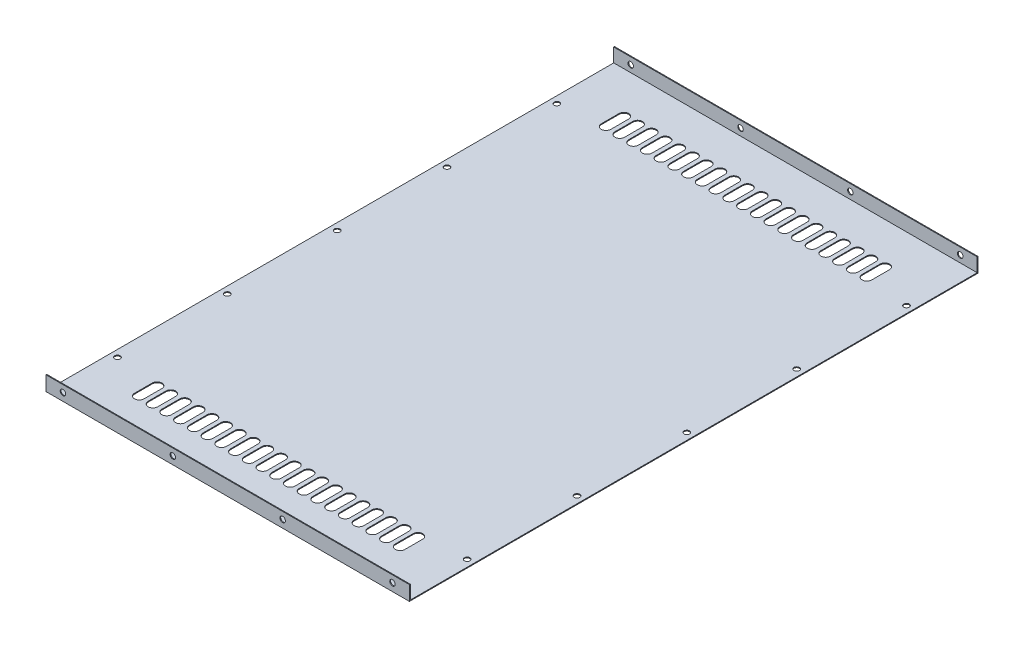
SolidWorks part; units mm, degrees
material "AISI 316 Нержавеющая сталь, лист (SS)"
ref_plane "Спереди" through (0, 0, 0) normal (0, 0, 1) x (1, 0, 0)
ref_plane "Сверху" through (0, 0, 0) normal (0, 1, 0) x (1, 0, 0)
ref_plane "Справа" through (0, 0, 0) normal (1, 0, 0) x (0, 0, -1)
other "Configuration Table"
sketch "Эскиз1" plane through (0, 0, 0) normal (0, 1, 0) x (1, 0, 0)
  line L0 (0, -207.05) -> (0, 207.05) construction
  line L1 (-132.35, 207.05) -> (132.35, 207.05)
  line L2 (-132.35, 207.05) -> (-132.35, -207.05)
  line L3 (-132.35, -207.05) -> (132.35, -207.05)
  line L4 (132.35, 207.05) -> (132.35, -207.05)
  line L5 (-132.35, 0) -> (132.35, 0) construction
  dimension "D1" = 414.1
  dimension "D2" = 264.7
extrude "Бобышка-Вытянуть1" add sketch "Эскиз1" along normal blind 0.6
sketch "Эскиз2" plane through (132.35, 0, 0) normal (1, 0, 0) x (0, 0, -1)
  line L1 (-207.05, 0) -> (-206.45, 0)
  line L2 (-207.05, 0) -> (-207.05, 10.6)
  line L3 (-207.05, 10.6) -> (-206.45, 10.6)
  line L4 (-206.45, 0) -> (-206.45, 10.6)
  line L5 (207.05, 0) -> (206.45, 0)
  line L6 (207.05, 0) -> (207.05, 10.6)
  line L7 (207.05, 10.6) -> (206.45, 10.6)
  line L8 (206.45, 0) -> (206.45, 10.6)
  dimension "D1" = 0.6
  dimension "D2" = 10.6
  dimension "D3" = 0.6
  dimension "D4" = 10.6
extrude "Бобышка-Вытянуть2" add sketch "Эскиз2" against normal up to surface (264.7 mm away) up to face at (-132.35, 0.3, 0)
sketch "Эскиз6" plane through (0, 0.6, 0) normal (0, 1, 0) x (1, 0, 0)
  line L0 (-132.35, 206.45) -> (-132.35, -206.45) construction
  line L1 (-132.35, -197.05) -> (-122.35, -197.05)
  line L2 (-132.35, -197.05) -> (-132.35, 197.05)
  line L3 (-132.35, 197.05) -> (-122.35, 197.05)
  line L4 (-122.35, -197.05) -> (-122.35, 197.05)
  line L5 (-132.35, 207.05) -> (132.35, 207.05) construction
  line L6 (-132.35, -207.05) -> (132.35, -207.05) construction
  line L7 (-127.35, -197.05) -> (-127.35, 197.05) construction
  line L8 (-132.35, 0) -> (-122.35, 0) construction
  line L9 (122.35, -197.05) -> (132.35, -197.05)
  line L10 (122.35, -197.05) -> (122.35, 197.05)
  line L11 (122.35, 197.05) -> (132.35, 197.05)
  line L12 (132.35, -197.05) -> (132.35, 197.05)
  line L13 (127.35, -197.05) -> (127.35, 197.05) construction
  line L14 (122.35, 0) -> (132.35, 0) construction
  line L15 (132.35, -206.45) -> (132.35, 206.45) construction
  circle A0 centre (-127.35, -160) radius 2
  circle A1 centre (-127.35, -80) radius 2
  circle A2 centre (-127.35, 0) radius 2
  circle A3 centre (-127.35, 80) radius 2
  circle A4 centre (-127.35, 160) radius 2
  circle A5 centre (127.35, -160) radius 2
  circle A6 centre (127.35, -80) radius 2
  circle A7 centre (127.35, 0) radius 2
  circle A8 centre (127.35, 80) radius 2
  circle A9 centre (127.35, 160) radius 2
  dimension "D4" = 4
  dimension "D7" = 4
  dimension "D1" = 10
  dimension "D2" = 10
  dimension "D3" = 10
  dimension "D6" = 80
  dimension "D8" = 80
  dimension "D9" = 10
  dimension "D10" = 10
  dimension "D11" = 10
  dimension "D12" = 80
  dimension "D13" = 80
  dimension "D14" = 80
  dimension "D5" = 5
extrude "Вырез-Вытянуть1" cut sketch "Эскиз6" against normal through all contours A6 | A5 | A7 | A8 | A9 | A1 | A2 | A0 | A3 | A4
sketch "Эскиз7" plane through (0, 0, -207.05) normal (0, 0, -1) x (-1, 0, 0)
  line L0 (-132.35, 0.6) -> (132.35, 0.6)
  line L1 (-132.35, 10.6) -> (-132.35, 0) construction
  line L2 (132.35, 10.6) -> (132.35, 0) construction
  line L3 (132.35, 10.6) -> (-132.35, 10.6) construction
  line L4 (-132.35, 5.6) -> (132.35, 5.6) construction
  line L5 (0, 10.6) -> (0, 0.6) construction
  circle A0 centre (-120, 5.6) radius 2
  circle A1 centre (-40, 5.6) radius 2
  circle A2 centre (40, 5.6) radius 2
  circle A3 centre (120, 5.6) radius 2
  dimension "D2" = 4
  dimension "D1" = 10
  dimension "D4" = 80
  dimension "D3" = 4
extrude "Вырез-Вытянуть2" cut sketch "Эскиз7" against normal up to surface (414.1 mm away) contours A0 | A1 | A2 | A3 up to face at (0, 5.3, 207.05)
sketch "Эскиз8" plane through (0, 0.6, 0) normal (0, 1, 0) x (1, 0, 0)
  line L0 (-95, 176.5) -> (-95, 163.5) construction
  line L1 (-91.5, 176.5) -> (-91.5, 163.5)
  line L2 (-98.5, 176.5) -> (-98.5, 163.5)
  line L3 (-85, 176.5) -> (-85, 163.5) construction
  line L4 (-81.5, 176.5) -> (-81.5, 163.5)
  line L5 (-88.5, 176.5) -> (-88.5, 163.5)
  line L6 (-75, 176.5) -> (-75, 163.5) construction
  line L7 (-71.5, 176.5) -> (-71.5, 163.5)
  line L8 (-78.5, 176.5) -> (-78.5, 163.5)
  line L9 (-65, 176.5) -> (-65, 163.5) construction
  line L10 (-61.5, 176.5) -> (-61.5, 163.5)
  line L11 (-68.5, 176.5) -> (-68.5, 163.5)
  line L12 (-55, 176.5) -> (-55, 163.5) construction
  line L13 (-51.5, 176.5) -> (-51.5, 163.5)
  line L14 (-58.5, 176.5) -> (-58.5, 163.5)
  line L15 (-45, 176.5) -> (-45, 163.5) construction
  line L16 (-41.5, 176.5) -> (-41.5, 163.5)
  line L17 (-48.5, 176.5) -> (-48.5, 163.5)
  line L18 (-35, 176.5) -> (-35, 163.5) construction
  line L19 (-31.5, 176.5) -> (-31.5, 163.5)
  line L20 (-38.5, 176.5) -> (-38.5, 163.5)
  line L21 (-25, 176.5) -> (-25, 163.5) construction
  line L22 (-21.5, 176.5) -> (-21.5, 163.5)
  line L23 (-28.5, 176.5) -> (-28.5, 163.5)
  line L24 (-15, 176.5) -> (-15, 163.5) construction
  line L25 (-11.5, 176.5) -> (-11.5, 163.5)
  line L26 (-18.5, 176.5) -> (-18.5, 163.5)
  line L27 (-5, 176.5) -> (-5, 163.5) construction
  line L28 (-1.5, 176.5) -> (-1.5, 163.5)
  line L29 (-8.5, 176.5) -> (-8.5, 163.5)
  line L30 (5, 176.5) -> (5, 163.5) construction
  line L31 (8.5, 176.5) -> (8.5, 163.5)
  line L32 (1.5, 176.5) -> (1.5, 163.5)
  line L33 (15, 176.5) -> (15, 163.5) construction
  line L34 (18.5, 176.5) -> (18.5, 163.5)
  line L35 (11.5, 176.5) -> (11.5, 163.5)
  line L36 (25, 176.5) -> (25, 163.5) construction
  line L37 (28.5, 176.5) -> (28.5, 163.5)
  line L38 (21.5, 176.5) -> (21.5, 163.5)
  line L39 (35, 176.5) -> (35, 163.5) construction
  line L40 (38.5, 176.5) -> (38.5, 163.5)
  line L41 (31.5, 176.5) -> (31.5, 163.5)
  line L42 (45, 176.5) -> (45, 163.5) construction
  line L43 (48.5, 176.5) -> (48.5, 163.5)
  line L44 (41.5, 176.5) -> (41.5, 163.5)
  line L45 (55, 176.5) -> (55, 163.5) construction
  line L46 (58.5, 176.5) -> (58.5, 163.5)
  line L47 (51.5, 176.5) -> (51.5, 163.5)
  line L48 (65, 176.5) -> (65, 163.5) construction
  line L49 (68.5, 176.5) -> (68.5, 163.5)
  line L50 (61.5, 176.5) -> (61.5, 163.5)
  line L51 (75, 176.5) -> (75, 163.5) construction
  line L52 (78.5, 176.5) -> (78.5, 163.5)
  line L53 (71.5, 176.5) -> (71.5, 163.5)
  line L54 (85, 176.5) -> (85, 163.5) construction
  line L55 (88.5, 176.5) -> (88.5, 163.5)
  line L56 (81.5, 176.5) -> (81.5, 163.5)
  line L57 (95, 176.5) -> (95, 163.5) construction
  line L58 (98.5, 176.5) -> (98.5, 163.5)
  line L59 (91.5, 176.5) -> (91.5, 163.5)
  line L60 (-85, -163.5) -> (-85, -176.5) construction
  line L61 (-81.5, -163.5) -> (-81.5, -176.5)
  line L62 (-88.5, -163.5) -> (-88.5, -176.5)
  line L63 (-75, -163.5) -> (-75, -176.5) construction
  line L64 (-71.5, -163.5) -> (-71.5, -176.5)
  line L65 (-78.5, -163.5) -> (-78.5, -176.5)
  line L66 (-65, -163.5) -> (-65, -176.5) construction
  line L67 (-61.5, -163.5) -> (-61.5, -176.5)
  line L68 (-68.5, -163.5) -> (-68.5, -176.5)
  line L69 (-55, -163.5) -> (-55, -176.5) construction
  line L70 (-51.5, -163.5) -> (-51.5, -176.5)
  line L71 (-58.5, -163.5) -> (-58.5, -176.5)
  line L72 (-45, -163.5) -> (-45, -176.5) construction
  line L73 (-41.5, -163.5) -> (-41.5, -176.5)
  line L74 (-48.5, -163.5) -> (-48.5, -176.5)
  line L75 (-35, -163.5) -> (-35, -176.5) construction
  line L76 (-31.5, -163.5) -> (-31.5, -176.5)
  line L77 (-38.5, -163.5) -> (-38.5, -176.5)
  line L78 (-25, -163.5) -> (-25, -176.5) construction
  line L79 (-21.5, -163.5) -> (-21.5, -176.5)
  line L80 (-28.5, -163.5) -> (-28.5, -176.5)
  line L81 (-15, -163.5) -> (-15, -176.5) construction
  line L82 (-11.5, -163.5) -> (-11.5, -176.5)
  line L83 (-18.5, -163.5) -> (-18.5, -176.5)
  line L84 (-5, -163.5) -> (-5, -176.5) construction
  line L85 (-1.5, -163.5) -> (-1.5, -176.5)
  line L86 (-8.5, -163.5) -> (-8.5, -176.5)
  line L87 (5, -163.5) -> (5, -176.5) construction
  line L88 (8.5, -163.5) -> (8.5, -176.5)
  line L89 (1.5, -163.5) -> (1.5, -176.5)
  line L90 (15, -163.5) -> (15, -176.5) construction
  line L91 (18.5, -163.5) -> (18.5, -176.5)
  line L92 (11.5, -163.5) -> (11.5, -176.5)
  line L93 (25, -163.5) -> (25, -176.5) construction
  line L94 (28.5, -163.5) -> (28.5, -176.5)
  line L95 (21.5, -163.5) -> (21.5, -176.5)
  line L96 (35, -163.5) -> (35, -176.5) construction
  line L97 (38.5, -163.5) -> (38.5, -176.5)
  line L98 (31.5, -163.5) -> (31.5, -176.5)
  line L99 (45, -163.5) -> (45, -176.5) construction
  line L100 (48.5, -163.5) -> (48.5, -176.5)
  line L101 (41.5, -163.5) -> (41.5, -176.5)
  line L102 (55, -163.5) -> (55, -176.5) construction
  line L103 (58.5, -163.5) -> (58.5, -176.5)
  line L104 (51.5, -163.5) -> (51.5, -176.5)
  line L105 (65, -163.5) -> (65, -176.5) construction
  line L106 (68.5, -163.5) -> (68.5, -176.5)
  line L107 (61.5, -163.5) -> (61.5, -176.5)
  line L108 (75, -163.5) -> (75, -176.5) construction
  line L109 (78.5, -163.5) -> (78.5, -176.5)
  line L110 (71.5, -163.5) -> (71.5, -176.5)
  line L111 (85, -163.5) -> (85, -176.5) construction
  line L112 (88.5, -163.5) -> (88.5, -176.5)
  line L113 (81.5, -163.5) -> (81.5, -176.5)
  line L114 (95, -163.5) -> (95, -176.5) construction
  line L115 (98.5, -163.5) -> (98.5, -176.5)
  line L116 (91.5, -163.5) -> (91.5, -176.5)
  line L117 (-95, -163.5) -> (-95, -176.5) construction
  line L118 (-91.5, -163.5) -> (-91.5, -176.5)
  line L119 (-98.5, -163.5) -> (-98.5, -176.5)
  line L120 (-132.35, 0) -> (132.35, 0) construction
  line L121 (-132.35, 206.45) -> (-132.35, -206.45) construction
  line L122 (132.35, -206.45) -> (132.35, 206.45) construction
  line L123 (0, 207.05) -> (0, -206.45) construction
  line L124 (-132.35, 207.05) -> (132.35, 207.05) construction
  line L125 (-132.35, -206.45) -> (132.35, -206.45) construction
  arc A0 (-91.5, 176.5) -> (-98.5, 176.5) centre (-95, 176.5) ccw
  arc A1 (-98.5, 163.5) -> (-91.5, 163.5) centre (-95, 163.5) ccw
  arc A2 (-81.5, 176.5) -> (-88.5, 176.5) centre (-85, 176.5) ccw
  arc A3 (-88.5, 163.5) -> (-81.5, 163.5) centre (-85, 163.5) ccw
  arc A4 (-71.5, 176.5) -> (-78.5, 176.5) centre (-75, 176.5) ccw
  arc A5 (-78.5, 163.5) -> (-71.5, 163.5) centre (-75, 163.5) ccw
  arc A6 (-61.5, 176.5) -> (-68.5, 176.5) centre (-65, 176.5) ccw
  arc A7 (-68.5, 163.5) -> (-61.5, 163.5) centre (-65, 163.5) ccw
  arc A8 (-51.5, 176.5) -> (-58.5, 176.5) centre (-55, 176.5) ccw
  arc A9 (-58.5, 163.5) -> (-51.5, 163.5) centre (-55, 163.5) ccw
  arc A10 (-41.5, 176.5) -> (-48.5, 176.5) centre (-45, 176.5) ccw
  arc A11 (-48.5, 163.5) -> (-41.5, 163.5) centre (-45, 163.5) ccw
  arc A12 (-31.5, 176.5) -> (-38.5, 176.5) centre (-35, 176.5) ccw
  arc A13 (-38.5, 163.5) -> (-31.5, 163.5) centre (-35, 163.5) ccw
  arc A14 (-21.5, 176.5) -> (-28.5, 176.5) centre (-25, 176.5) ccw
  arc A15 (-28.5, 163.5) -> (-21.5, 163.5) centre (-25, 163.5) ccw
  arc A16 (-11.5, 176.5) -> (-18.5, 176.5) centre (-15, 176.5) ccw
  arc A17 (-18.5, 163.5) -> (-11.5, 163.5) centre (-15, 163.5) ccw
  arc A18 (-1.5, 176.5) -> (-8.5, 176.5) centre (-5, 176.5) ccw
  arc A19 (-8.5, 163.5) -> (-1.5, 163.5) centre (-5, 163.5) ccw
  arc A20 (8.5, 176.5) -> (1.5, 176.5) centre (5, 176.5) ccw
  arc A21 (1.5, 163.5) -> (8.5, 163.5) centre (5, 163.5) ccw
  arc A22 (18.5, 176.5) -> (11.5, 176.5) centre (15, 176.5) ccw
  arc A23 (11.5, 163.5) -> (18.5, 163.5) centre (15, 163.5) ccw
  arc A24 (28.5, 176.5) -> (21.5, 176.5) centre (25, 176.5) ccw
  arc A25 (21.5, 163.5) -> (28.5, 163.5) centre (25, 163.5) ccw
  arc A26 (38.5, 176.5) -> (31.5, 176.5) centre (35, 176.5) ccw
  arc A27 (31.5, 163.5) -> (38.5, 163.5) centre (35, 163.5) ccw
  arc A28 (48.5, 176.5) -> (41.5, 176.5) centre (45, 176.5) ccw
  arc A29 (41.5, 163.5) -> (48.5, 163.5) centre (45, 163.5) ccw
  arc A30 (58.5, 176.5) -> (51.5, 176.5) centre (55, 176.5) ccw
  arc A31 (51.5, 163.5) -> (58.5, 163.5) centre (55, 163.5) ccw
  arc A32 (68.5, 176.5) -> (61.5, 176.5) centre (65, 176.5) ccw
  arc A33 (61.5, 163.5) -> (68.5, 163.5) centre (65, 163.5) ccw
  arc A34 (78.5, 176.5) -> (71.5, 176.5) centre (75, 176.5) ccw
  arc A35 (71.5, 163.5) -> (78.5, 163.5) centre (75, 163.5) ccw
  arc A36 (88.5, 176.5) -> (81.5, 176.5) centre (85, 176.5) ccw
  arc A37 (81.5, 163.5) -> (88.5, 163.5) centre (85, 163.5) ccw
  arc A38 (98.5, 176.5) -> (91.5, 176.5) centre (95, 176.5) ccw
  arc A39 (91.5, 163.5) -> (98.5, 163.5) centre (95, 163.5) ccw
  arc A40 (-81.5, -163.5) -> (-88.5, -163.5) centre (-85, -163.5) ccw
  arc A41 (-88.5, -176.5) -> (-81.5, -176.5) centre (-85, -176.5) ccw
  arc A42 (-71.5, -163.5) -> (-78.5, -163.5) centre (-75, -163.5) ccw
  arc A43 (-78.5, -176.5) -> (-71.5, -176.5) centre (-75, -176.5) ccw
  arc A44 (-61.5, -163.5) -> (-68.5, -163.5) centre (-65, -163.5) ccw
  arc A45 (-68.5, -176.5) -> (-61.5, -176.5) centre (-65, -176.5) ccw
  arc A46 (-51.5, -163.5) -> (-58.5, -163.5) centre (-55, -163.5) ccw
  arc A47 (-58.5, -176.5) -> (-51.5, -176.5) centre (-55, -176.5) ccw
  arc A48 (-41.5, -163.5) -> (-48.5, -163.5) centre (-45, -163.5) ccw
  arc A49 (-48.5, -176.5) -> (-41.5, -176.5) centre (-45, -176.5) ccw
  arc A50 (-31.5, -163.5) -> (-38.5, -163.5) centre (-35, -163.5) ccw
  arc A51 (-38.5, -176.5) -> (-31.5, -176.5) centre (-35, -176.5) ccw
  arc A52 (-21.5, -163.5) -> (-28.5, -163.5) centre (-25, -163.5) ccw
  arc A53 (-28.5, -176.5) -> (-21.5, -176.5) centre (-25, -176.5) ccw
  arc A54 (-11.5, -163.5) -> (-18.5, -163.5) centre (-15, -163.5) ccw
  arc A55 (-18.5, -176.5) -> (-11.5, -176.5) centre (-15, -176.5) ccw
  arc A56 (-1.5, -163.5) -> (-8.5, -163.5) centre (-5, -163.5) ccw
  arc A57 (-8.5, -176.5) -> (-1.5, -176.5) centre (-5, -176.5) ccw
  arc A58 (8.5, -163.5) -> (1.5, -163.5) centre (5, -163.5) ccw
  arc A59 (1.5, -176.5) -> (8.5, -176.5) centre (5, -176.5) ccw
  arc A60 (18.5, -163.5) -> (11.5, -163.5) centre (15, -163.5) ccw
  arc A61 (11.5, -176.5) -> (18.5, -176.5) centre (15, -176.5) ccw
  arc A62 (28.5, -163.5) -> (21.5, -163.5) centre (25, -163.5) ccw
  arc A63 (21.5, -176.5) -> (28.5, -176.5) centre (25, -176.5) ccw
  arc A64 (38.5, -163.5) -> (31.5, -163.5) centre (35, -163.5) ccw
  arc A65 (31.5, -176.5) -> (38.5, -176.5) centre (35, -176.5) ccw
  arc A66 (48.5, -163.5) -> (41.5, -163.5) centre (45, -163.5) ccw
  arc A67 (41.5, -176.5) -> (48.5, -176.5) centre (45, -176.5) ccw
  arc A68 (58.5, -163.5) -> (51.5, -163.5) centre (55, -163.5) ccw
  arc A69 (51.5, -176.5) -> (58.5, -176.5) centre (55, -176.5) ccw
  arc A70 (68.5, -163.5) -> (61.5, -163.5) centre (65, -163.5) ccw
  arc A71 (61.5, -176.5) -> (68.5, -176.5) centre (65, -176.5) ccw
  arc A72 (78.5, -163.5) -> (71.5, -163.5) centre (75, -163.5) ccw
  arc A73 (71.5, -176.5) -> (78.5, -176.5) centre (75, -176.5) ccw
  arc A74 (88.5, -163.5) -> (81.5, -163.5) centre (85, -163.5) ccw
  arc A75 (81.5, -176.5) -> (88.5, -176.5) centre (85, -176.5) ccw
  arc A76 (98.5, -163.5) -> (91.5, -163.5) centre (95, -163.5) ccw
  arc A77 (91.5, -176.5) -> (98.5, -176.5) centre (95, -176.5) ccw
  arc A78 (-91.5, -163.5) -> (-98.5, -163.5) centre (-95, -163.5) ccw
  arc A79 (-98.5, -176.5) -> (-91.5, -176.5) centre (-95, -176.5) ccw
  point P2 (-95, 170)
  point P7 (-95, 180)
  point P8 (-95, 160)
  point P14 (-85, 170)
  point P21 (-75, 170)
  point P28 (-65, 170)
  point P35 (-55, 170)
  point P42 (-45, 170)
  point P49 (-35, 170)
  point P56 (-25, 170)
  point P63 (-15, 170)
  point P70 (-5, 170)
  point P77 (5, 170)
  point P84 (15, 170)
  point P91 (25, 170)
  point P98 (35, 170)
  point P105 (45, 170)
  point P112 (55, 170)
  point P119 (65, 170)
  point P126 (75, 170)
  point P133 (85, 170)
  point P140 (95, 170)
  point P147 (-85, -170)
  point P154 (-75, -170)
  point P161 (-65, -170)
  point P168 (-55, -170)
  point P175 (-45, -170)
  point P182 (-35, -170)
  point P189 (-25, -170)
  point P196 (-15, -170)
  point P203 (-5, -170)
  point P210 (5, -170)
  point P217 (15, -170)
  point P224 (25, -170)
  point P231 (35, -170)
  point P238 (45, -170)
  point P245 (55, -170)
  point P252 (65, -170)
  point P259 (75, -170)
  point P266 (85, -170)
  point P273 (95, -170)
  point P280 (-95, -170)
  dimension "D1" = 20
  dimension "D2" = 7
  dimension "D5" = 340
  dimension "D6" = 10
  dimension "D7" = 5
  dimension "D3" = 20
  dimension "D4" = 2
extrude "Вырез-Вытянуть4" cut sketch "Эскиз8" against normal through all
